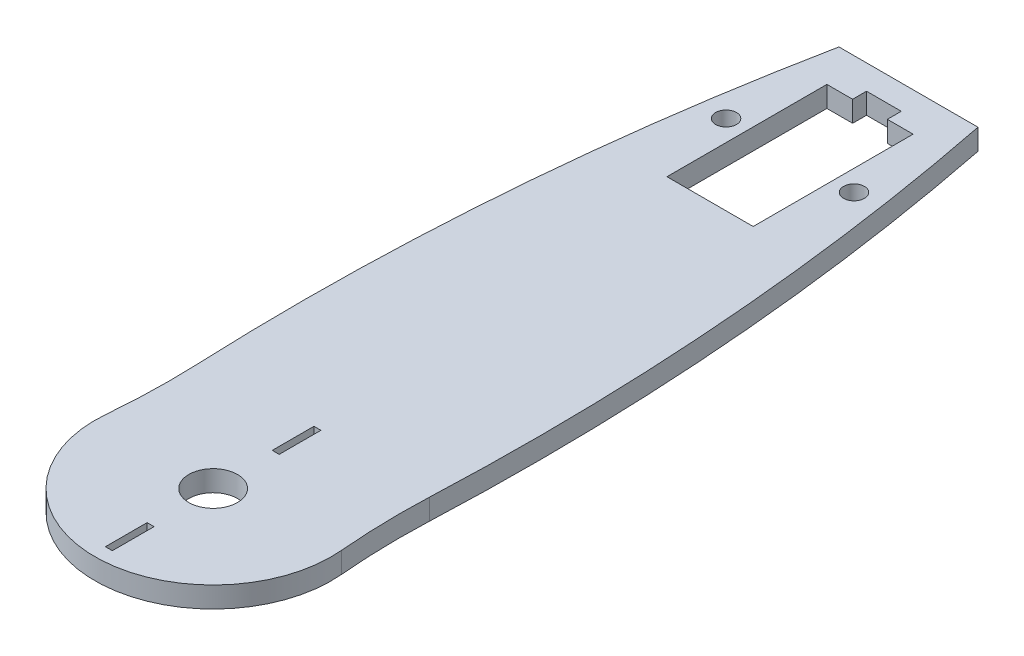
SolidWorks part; units mm, degrees
material "Cedro"
ref_plane "Plano frontal" through (0, 0, 0) normal (0, 0, 1) x (1, 0, 0)
ref_plane "Plano superior" through (0, 0, 0) normal (0, 1, 0) x (1, 0, 0)
ref_plane "Plano direito" through (0, 0, 0) normal (1, 0, 0) x (0, 0, -1)
sketch "Esboço4" plane through (0, 0, 0) normal (0, 1, 0) x (1, 0, 0)
  line L0 (6.2, 94.4666) -> (6.2, 71.4666)
  line L1 (6.2, 71.4666) -> (-6.2, 71.4666)
  line L2 (-6.2, 71.4666) -> (-6.2, 94.4666)
  line L3 (6.2, 94.4666) -> (2.5, 94.4666)
  line L4 (-6.2, 94.4666) -> (-2.5, 94.4666)
  line L5 (2.5, 94.4666) -> (2.5, 96.4666)
  line L6 (2.5, 96.4666) -> (-2.5, 96.4666)
  line L7 (0, -15) -> (-0.5, -15)
  line L8 (-0.5, -15) -> (-0.5, -9)
  line L9 (-0.5, -9) -> (0.5, -9)
  line L10 (0.5, -9) -> (0.5, -15)
  line L11 (0.5, -15) -> (0, -15)
  line L12 (0.5, 15) -> (0, 15)
  line L13 (0.5, 9) -> (0.5, 15)
  line L14 (-0.5, 9) -> (0.5, 9)
  line L15 (-0.5, 15) -> (-0.5, 9)
  line L16 (0, 15) -> (-0.5, 15)
  line L17 (-2.5, 96.4666) -> (-2.5, 94.4666)
  line L19 (0, 100) -> (10, 100)
  line L21 (0, 100) -> (-10, 100)
  circle A0 centre (0, 0) radius 3.5
  arc A1 (-16.9338, 1.4991) -> (16.9338, 1.4991) centre (0, 0) ccw
  arc A2 (-10, 100) -> (-16.6323, 14.5129) centre (342.9769, 29.6144) ccw
  arc A3 (10, 100) -> (16.6323, 14.5129) centre (-342.9769, 29.6144) cw
  circle A4 centre (9.2, 82.9666) radius 1.5
  arc A5 (-16.9338, 1.4991) -> (-16.6323, 14.5129) centre (-116.5442, 10.3172) ccw
  circle A6 centre (-9.2, 82.9666) radius 1.5
  arc A7 (16.9338, 1.4991) -> (16.6323, 14.5129) centre (116.5442, 10.3172) cw
  dimension "D1" = 100
  dimension "D2" = 100
extrude "Ressalto-extrusão1" add sketch "Esboço4" along normal blind 3
